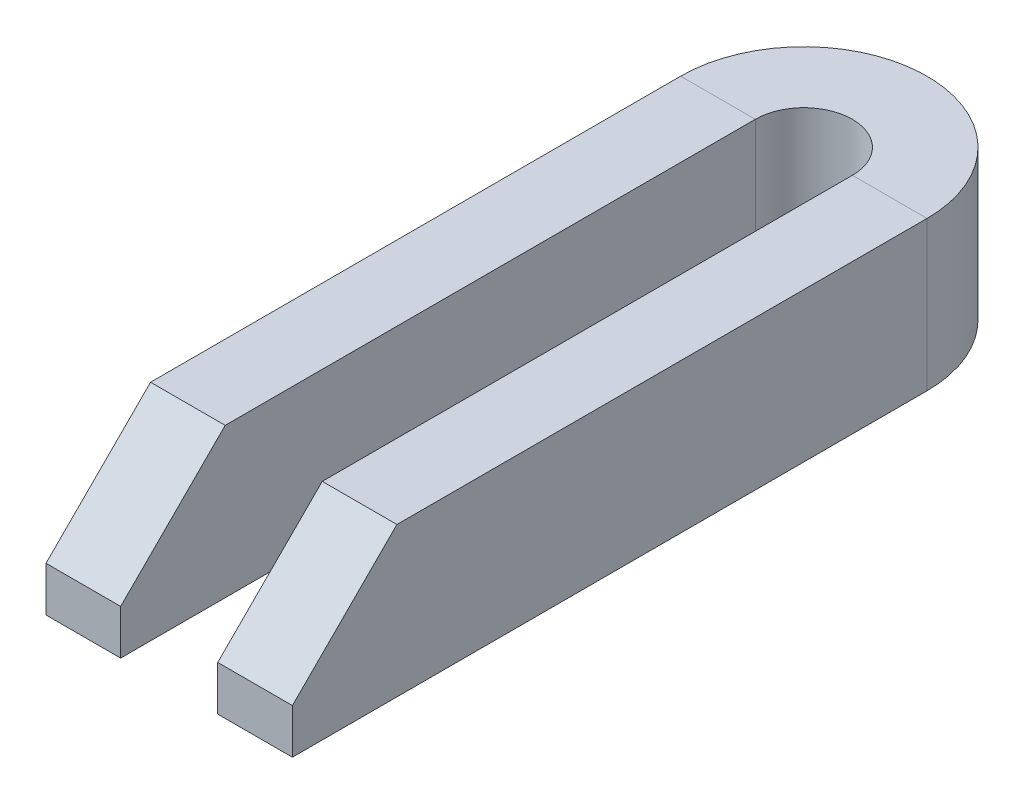
SolidWorks part; units mm, degrees
ref_plane "Front Plane" through (0, 0, 0) normal (0, 0, 1) x (1, 0, 0)
ref_plane "Top Plane" through (0, 0, 0) normal (0, 1, 0) x (1, 0, 0)
ref_plane "Right Plane" through (0, 0, 0) normal (1, 0, 0) x (0, 0, -1)
sketch "Sketch1" plane through (0, 0, 0) normal (0, 0, 1) x (1, 0, 0)
  line L0 (-13, 0) -> (-13, 40)
  line L1 (-13, 40) -> (-33, 40)
  line L2 (-33, 40) -> (-33, 0)
  line L3 (-33, 0) -> (-13, 0)
  line L4 (0, 0) -> (0, 50.2817) construction
  dimension "Korkeus" = 40
  dimension "Aukonleveys" = 26
  dimension "Leveys" = 66
sketch "Sketch2" plane through (0, 0, 0) normal (0, 1, 0) x (1, 0, 0)
  line L0 (-13, 0) -> (-13, 170)
  line L2 (-14.1817, 183) -> (25.9918, 183) construction
  line L3 (13, 170) -> (13, 0)
  line L4 (0, 0) -> (0, 170) construction
  line L5 (0, 183) -> (0, 203) construction
  line L6 (-33, 0) -> (-13, 0) construction
  line L7 (-33, 0) -> (-13, 0) construction
  arc A0 (-13, 170) -> (13, 170) centre (0, 170) cw
  dimension "SakaranPituus" = 170
  dimension "D1" = 203
  dimension "D2" = 13
  dimension "D3" = 33
sweep "Sweep1" add profiles "Sketch1" path "Sketch2"
chamfer "Chamfer1" distance 28 angle 45 2 edges at (-23, 40, 0) (23, 40, 0)
equation "\"_leveys\" = \"Leveys@Sketch1\""
equation "\"_aukonLeveys\" = \"Aukonleveys@Sketch1\""
equation "\"_korkeus\" = \"Korkeus@Sketch1\""
equation "\"_sakaranPituus\" = \"SakaranPituus@Sketch2\""
equation "\"_viiste\" = \"Viiste@Chamfer1\""
equation "\"_kokonaisPituus\" = \"_sakaranPituus\" + ( \"_leveys\" - \"_aukonLeveys\" ) / 2 + \"_aukonLeveys\" / 2"
